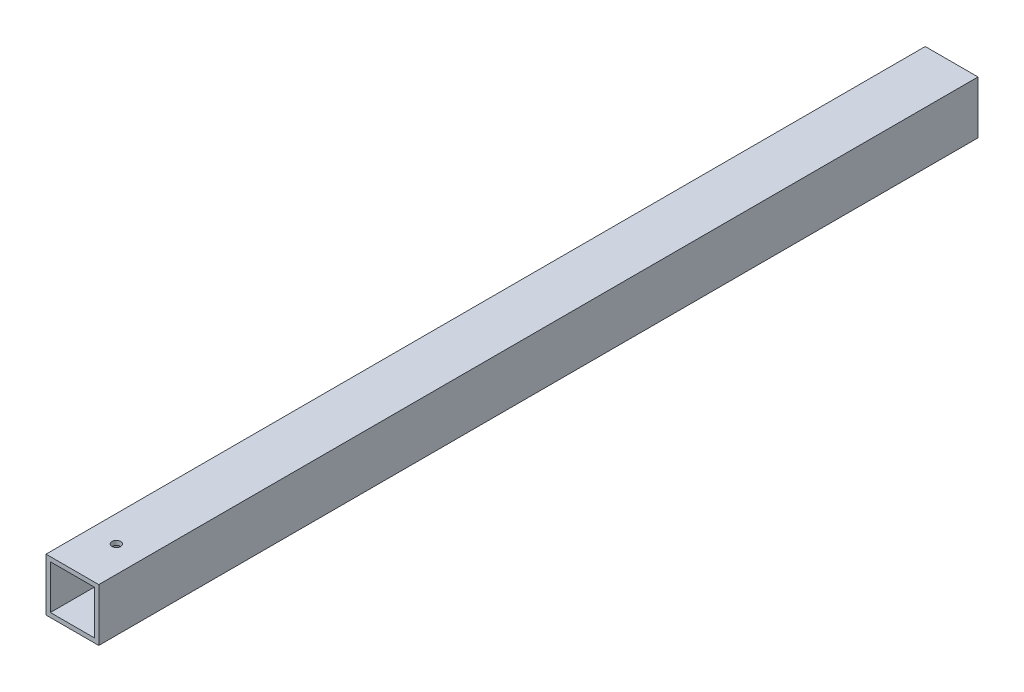
SolidWorks part; units mm, degrees
ref_plane "前视基准面" through (0, 0, 0) normal (0, 0, 1) x (1, 0, 0)
ref_plane "上视基准面" through (0, 0, 0) normal (0, 1, 0) x (1, 0, 0)
ref_plane "右视基准面" through (0, 0, 0) normal (1, 0, 0) x (0, 0, -1)
sketch "草图1" plane through (0, 0, 0) normal (0, 0, 1) x (1, 0, 0)
  line L1 (0, 0) -> (12, 0)
  line L2 (0, 0) -> (0, 12)
  line L3 (0, 12) -> (12, 12)
  line L4 (12, 0) -> (12, 12)
  line L5 (1, 1) -> (11, 1)
  line L6 (1, 1) -> (1, 11)
  line L7 (1, 11) -> (11, 11)
  line L8 (11, 1) -> (11, 11)
  point P5 (1, 1)
extrude "凸台-拉伸1" add sketch "草图1" along normal blind 200
sketch "草图2" plane through (0, 0, 0) normal (0, -1, 0) x (1, 0, 0)
  circle A0 centre (6, 190) radius 1
  point P0 (6, 190)
extrude "切除-拉伸1" cut sketch "草图2" against normal blind 12
